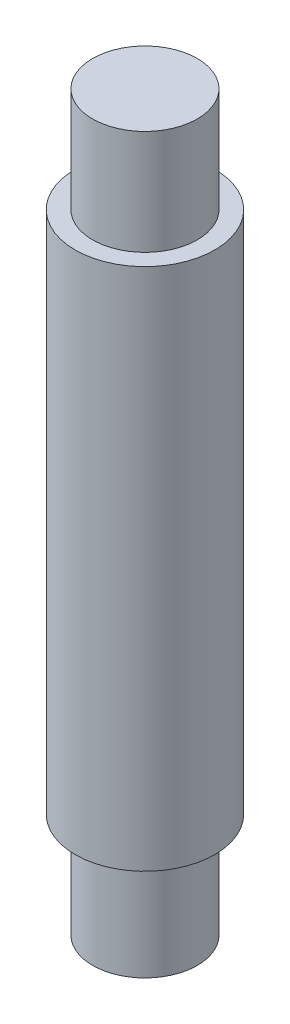
SolidWorks part; units mm, degrees
ref_plane "Front Plane" through (0, 0, 0) normal (0, 0, 1) x (1, 0, 0)
ref_plane "Top Plane" through (0, 0, 0) normal (0, 1, 0) x (1, 0, 0)
ref_plane "Right Plane" through (0, 0, 0) normal (1, 0, 0) x (0, 0, -1)
sketch "Sketch1" plane through (0, 0, 0) normal (0, 1, 0) x (1, 0, 0)
  circle A0 centre (0, 0) radius 76.2
  dimension "D1" = 152.4
extrude "Boss-Extrude1" add sketch "Sketch1" along normal blind 152.4
sketch "Sketch2" plane through (0, 152.4, 0) normal (0, 1, 0) x (1, 0, 0)
  circle A0 centre (0, 0) radius 101.6
  dimension "D1" = 203.2
extrude "Boss-Extrude2" add sketch "Sketch2" along normal blind 762
sketch "Sketch3" plane through (0, 914.4, 0) normal (0, 1, 0) x (1, 0, 0)
  circle A0 centre (0, 0) radius 76.2
  dimension "D1" = 152.4
extrude "Boss-Extrude3" add sketch "Sketch3" along normal blind 152.4
